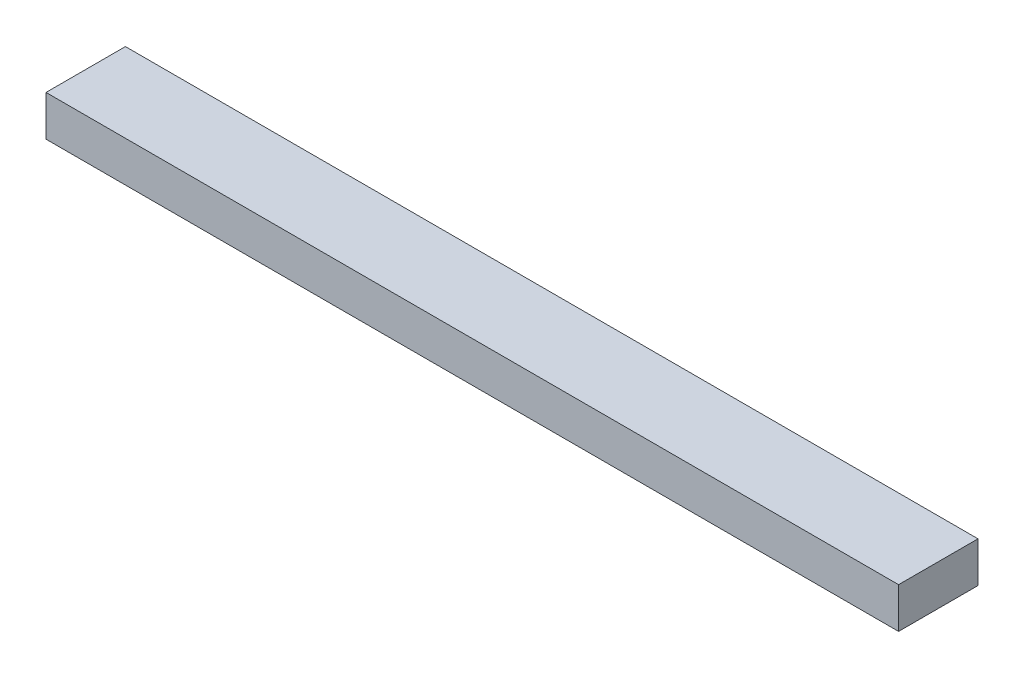
SolidWorks part; units mm, degrees
ref_plane "Front Plane" through (0, 0, 0) normal (0, 0, 1) x (1, 0, 0)
ref_plane "Top Plane" through (0, 0, 0) normal (0, 1, 0) x (1, 0, 0)
ref_plane "Right Plane" through (0, 0, 0) normal (1, 0, 0) x (0, 0, -1)
sketch "Sketch1" plane through (0, 0, 0) normal (0, 0, 1) x (1, 0, 0)
  line L0 (184.0657, 100.017) -> (184.0657, -29.983) construction
  line L1 (184.0657, -25.283) -> (451.3657, -25.283)
  line L2 (184.0657, -25.283) -> (184.0657, -37.983)
  line L3 (184.0657, -37.983) -> (451.3657, -37.983)
  line L4 (451.3657, -25.283) -> (451.3657, -37.983)
  line L5 (176.0657, -37.983) -> (46.0657, -37.983) construction
  line L6 (184.0657, 242.017) -> (464.0657, 242.017) construction
  line L7 (184.0657, 242.017) -> (184.0657, -37.983) construction
  line L8 (184.0657, -37.983) -> (464.0657, -37.983) construction
  line L9 (464.0657, 242.017) -> (464.0657, -37.983) construction
  line L10 (46.0657, 242.017) -> (176.0657, 242.017) construction
  line L11 (184.0657, 234.017) -> (184.0657, 104.017) construction
  dimension "D1" = 12.7
  dimension "D2" = 12.7
extrude "Boss-Extrude1" add sketch "Sketch1" along normal up to surface (24.9 mm away)
equation "\"wood_thickness\"= 0.5in"
equation "\"D1@Sketch1\"=\"wood_thickness\""
equation "\"D2@Sketch1\"=\"wood_thickness\""
